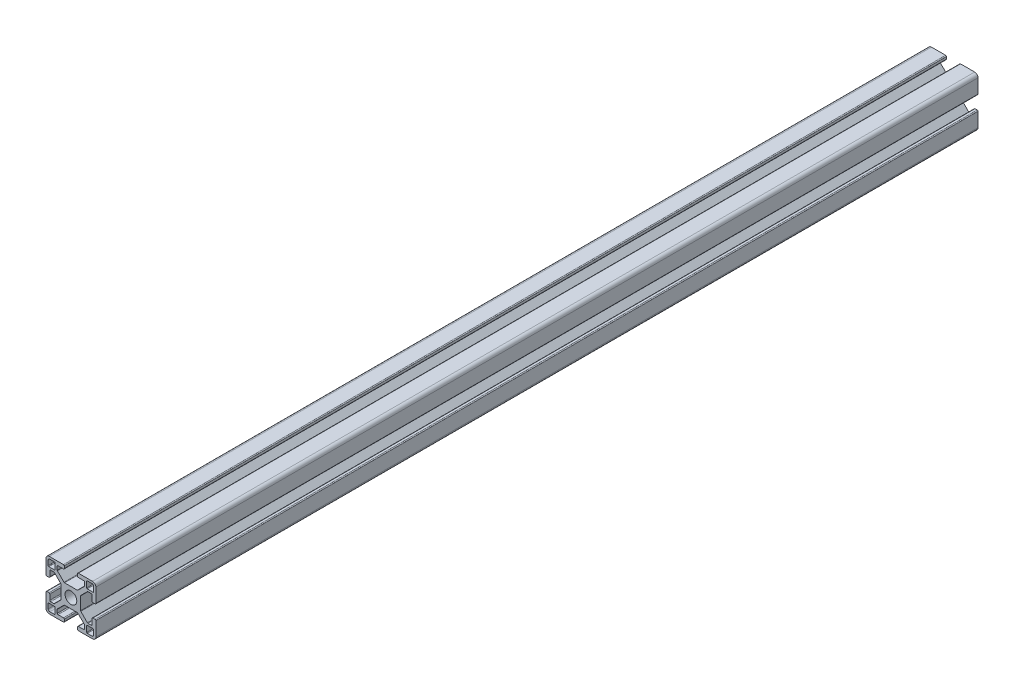
SolidWorks part; units mm, degrees
ref_plane "Front Plane" through (0, 0, 0) normal (0, 0, 1) x (1, 0, 0)
ref_plane "Top Plane" through (0, 0, 0) normal (0, 1, 0) x (1, 0, 0)
ref_plane "Right Plane" through (0, 0, 0) normal (1, 0, 0) x (0, 0, -1)
sketch "Sketch1" plane through (0, 0, 0) normal (0, 0, 1) x (1, 0, 0)
  line L0 (3.9799, -2.4733) -> (3.1981, -1.4942) construction
  line L1 (1.4942, -3.1981) -> (2.4733, -3.9799) construction
  line L2 (-2.4733, -3.9799) -> (-1.4942, -3.1981) construction
  line L3 (-3.1981, -1.4942) -> (-3.9799, -2.4733) construction
  line L4 (-3.9799, 2.4733) -> (-3.1981, 1.4942) construction
  line L5 (-1.4942, 3.1981) -> (-2.4733, 3.9799) construction
  line L6 (2.4733, 3.9799) -> (1.4942, 3.1981) construction
  line L7 (3.1981, 1.4942) -> (3.9799, 2.4733) construction
  line L8 (-12.6999, -13.6999) -> (-9.881, -13.6999)
  line L9 (-13.6999, -9.881) -> (-13.6999, -12.6999)
  line L10 (-9.88, -9.5) -> (-13.3189, -9.5)
  line L11 (-9.5, -13.3189) -> (-9.5, -9.88)
  line L12 (13.6999, -12.6999) -> (13.6999, -9.881)
  line L13 (9.881, -13.6999) -> (12.6999, -13.6999)
  line L14 (9.5, -9.88) -> (9.5, -13.3189)
  line L15 (13.3189, -9.5) -> (9.88, -9.5)
  line L16 (9.88, 9.5) -> (13.3189, 9.5)
  line L17 (9.5, 13.3189) -> (9.5, 9.88)
  line L18 (12.6999, 13.6999) -> (9.881, 13.6999)
  line L19 (13.6999, 9.881) -> (13.6999, 12.6999)
  line L20 (-13.6999, 12.6999) -> (-13.6999, 9.881)
  line L21 (-9.881, 13.6999) -> (-12.6999, 13.6999)
  line L22 (-9.5, 9.88) -> (-9.5, 13.3189)
  line L23 (-13.3189, 9.5) -> (-9.88, 9.5)
  line L24 (14.4999, -4) -> (13.2425, -4)
  line L25 (12.7425, -4.5) -> (12.7425, -7.7325)
  line L26 (12.2428, -8.25) -> (10.2602, -8.25)
  line L27 (9.9066, -8.1035) -> (5.9811, -4.178)
  line L28 (5.8347, -3.8245) -> (5.8347, -1.0125)
  line L29 (5.8347, -1.0125) -> (5.3247, -0.0625) construction
  line L30 (5.3247, -0.0625) -> (5.8347, 0.8875) construction
  line L31 (5.8347, 0.8875) -> (5.8347, 3.8245)
  line L32 (5.9811, 4.178) -> (9.9066, 8.1035)
  line L33 (10.2602, 8.25) -> (12.2428, 8.25)
  line L34 (12.7425, 7.7325) -> (12.7425, 4.5)
  line L35 (13.2425, 4) -> (14.4999, 4)
  line L36 (14.9999, 4.5) -> (14.9999, 12.9999)
  line L37 (12.9999, 14.9999) -> (4.5, 14.9999)
  line L38 (4, 14.4999) -> (4, 13.2425)
  line L39 (4.5, 12.7425) -> (7.7325, 12.7425)
  line L40 (8.25, 12.2428) -> (8.25, 10.2602)
  line L41 (8.1035, 9.9066) -> (4.178, 5.9811)
  line L42 (3.8245, 5.8347) -> (0.95, 5.8347)
  line L43 (0.95, 5.8347) -> (0, 5.3247) construction
  line L44 (0, 5.3247) -> (-0.95, 5.8347) construction
  line L45 (-0.95, 5.8347) -> (-3.8245, 5.8347)
  line L46 (-4.178, 5.9811) -> (-8.1035, 9.9066)
  line L47 (-8.25, 10.2602) -> (-8.25, 12.2428)
  line L48 (-7.7325, 12.7425) -> (-4.5, 12.7425)
  line L49 (-4, 13.2425) -> (-4, 14.4999)
  line L50 (-4.5, 14.9999) -> (-12.9999, 14.9999)
  line L51 (-14.9999, 12.9999) -> (-14.9999, 4.5)
  line L52 (-14.4999, 4) -> (-13.2425, 4)
  line L53 (-12.7425, 4.5) -> (-12.7425, 7.7325)
  line L54 (-12.2428, 8.25) -> (-10.2602, 8.25)
  line L55 (-9.9066, 8.1035) -> (-5.9811, 4.178)
  line L56 (-5.8347, 3.8245) -> (-5.8347, 0.8875)
  line L57 (-5.8347, 0.8875) -> (-5.3247, -0.0625) construction
  line L58 (-5.3247, -0.0625) -> (-5.8347, -1.0125) construction
  line L59 (-5.8347, -1.0125) -> (-5.8347, -3.8245)
  line L60 (-5.9811, -4.178) -> (-9.9066, -8.1035)
  line L61 (-10.2602, -8.25) -> (-12.2428, -8.25)
  line L62 (-12.7425, -7.7325) -> (-12.7425, -4.5)
  line L63 (-13.2425, -4) -> (-14.4999, -4)
  line L64 (-14.9999, -4.5) -> (-14.9999, -12.9999)
  line L65 (-12.9999, -14.9999) -> (-4.5, -14.9999)
  line L66 (-4, -14.4999) -> (-4, -13.2425)
  line L67 (-4.5, -12.7425) -> (-7.7325, -12.7425)
  line L68 (-8.25, -12.2428) -> (-8.25, -10.2602)
  line L69 (-8.1035, -9.9066) -> (-4.178, -5.9811)
  line L70 (-3.8245, -5.8347) -> (-0.95, -5.8347)
  line L71 (-0.95, -5.8347) -> (0, -5.3247) construction
  line L72 (0, -5.3247) -> (0.95, -5.8347) construction
  line L73 (0.95, -5.8347) -> (3.8245, -5.8347)
  line L74 (4.178, -5.9811) -> (8.1035, -9.9066)
  line L75 (8.25, -10.2602) -> (8.25, -12.2428)
  line L76 (7.7325, -12.7425) -> (4.5, -12.7425)
  line L77 (4, -13.2425) -> (4, -14.4999)
  line L78 (4.5, -14.9999) -> (12.9999, -14.9999)
  line L79 (14.9999, -12.9999) -> (14.9999, -4.5)
  line L80 (-5.8347, -1.0125) -> (-5.8347, 0.8875)
  line L81 (-0.95, 5.8347) -> (0.95, 5.8347)
  line L82 (5.8347, 0.8875) -> (5.8347, -1.0125)
  line L83 (-0.95, -5.8347) -> (0.95, -5.8347)
  arc A0 (2.4733, -3.9799) -> (3.9799, -2.4733) centre (3.1422, -3.1422) ccw construction
  arc A1 (-1.4942, -3.1981) -> (1.4942, -3.1981) centre (0, 0) ccw construction
  arc A2 (-3.9799, -2.4733) -> (-2.4733, -3.9799) centre (-3.1422, -3.1422) ccw construction
  arc A3 (-3.1981, 1.4942) -> (-3.1981, -1.4942) centre (0, 0) ccw construction
  arc A4 (-2.4733, 3.9799) -> (-3.9799, 2.4733) centre (-3.1422, 3.1422) ccw construction
  arc A5 (1.4942, 3.1981) -> (-1.4942, 3.1981) centre (0, 0) ccw construction
  arc A6 (3.9799, 2.4733) -> (2.4733, 3.9799) centre (3.1422, 3.1422) ccw construction
  arc A7 (3.1981, -1.4942) -> (3.1981, 1.4942) centre (0, 0) ccw construction
  arc A8 (-13.6999, -12.6999) -> (-12.6999, -13.6999) centre (-12.6999, -12.6999) ccw
  arc A9 (-13.3189, -9.5) -> (-13.6999, -9.881) centre (-13.3189, -9.881) ccw
  arc A10 (-9.5, -9.88) -> (-9.88, -9.5) centre (-9.88, -9.88) ccw
  arc A11 (-9.881, -13.6999) -> (-9.5, -13.3189) centre (-9.881, -13.3189) ccw
  arc A12 (12.6999, -13.6999) -> (13.6999, -12.6999) centre (12.6999, -12.6999) ccw
  arc A13 (9.5, -13.3189) -> (9.881, -13.6999) centre (9.881, -13.3189) ccw
  arc A14 (9.88, -9.5) -> (9.5, -9.88) centre (9.88, -9.88) ccw
  arc A15 (13.6999, -9.881) -> (13.3189, -9.5) centre (13.3189, -9.881) ccw
  arc A16 (9.5, 9.88) -> (9.88, 9.5) centre (9.88, 9.88) ccw
  arc A17 (9.881, 13.6999) -> (9.5, 13.3189) centre (9.881, 13.3189) ccw
  arc A18 (13.6999, 12.6999) -> (12.6999, 13.6999) centre (12.6999, 12.6999) ccw
  arc A19 (13.3189, 9.5) -> (13.6999, 9.881) centre (13.3189, 9.881) ccw
  arc A20 (14.9999, -4.5) -> (14.4999, -4) centre (14.4999, -4.5) ccw
  arc A21 (13.2425, -4) -> (12.7425, -4.5) centre (13.2425, -4.5) ccw
  arc A22 (12.2428, -8.25) -> (12.7425, -7.7325) centre (12.2428, -7.75) ccw
  arc A23 (9.9066, -8.1035) -> (10.2602, -8.25) centre (10.2602, -7.75) ccw
  arc A24 (5.8347, -3.8245) -> (5.9811, -4.178) centre (6.3347, -3.8245) ccw
  arc A25 (5.9811, 4.178) -> (5.8347, 3.8245) centre (6.3347, 3.8245) ccw
  arc A26 (10.2602, 8.25) -> (9.9066, 8.1035) centre (10.2602, 7.75) ccw
  arc A27 (12.7425, 7.7325) -> (12.2428, 8.25) centre (12.2428, 7.75) ccw
  arc A28 (12.7425, 4.5) -> (13.2425, 4) centre (13.2425, 4.5) ccw
  arc A29 (14.4999, 4) -> (14.9999, 4.5) centre (14.4999, 4.5) ccw
  arc A30 (14.9999, 12.9999) -> (12.9999, 14.9999) centre (12.9999, 12.9999) ccw
  arc A31 (4.5, 14.9999) -> (4, 14.4999) centre (4.5, 14.4999) ccw
  arc A32 (4, 13.2425) -> (4.5, 12.7425) centre (4.5, 13.2425) ccw
  arc A33 (8.25, 12.2428) -> (7.7325, 12.7425) centre (7.75, 12.2428) ccw
  arc A34 (8.1035, 9.9066) -> (8.25, 10.2602) centre (7.75, 10.2602) ccw
  arc A35 (3.8245, 5.8347) -> (4.178, 5.9811) centre (3.8245, 6.3347) ccw
  arc A36 (-4.178, 5.9811) -> (-3.8245, 5.8347) centre (-3.8245, 6.3347) ccw
  arc A37 (-8.25, 10.2602) -> (-8.1035, 9.9066) centre (-7.75, 10.2602) ccw
  arc A38 (-7.7325, 12.7425) -> (-8.25, 12.2428) centre (-7.75, 12.2428) ccw
  arc A39 (-4.5, 12.7425) -> (-4, 13.2425) centre (-4.5, 13.2425) ccw
  arc A40 (-4, 14.4999) -> (-4.5, 14.9999) centre (-4.5, 14.4999) ccw
  arc A41 (-12.9999, 14.9999) -> (-14.9999, 12.9999) centre (-12.9999, 12.9999) ccw
  arc A42 (-14.9999, 4.5) -> (-14.4999, 4) centre (-14.4999, 4.5) ccw
  arc A43 (-13.2425, 4) -> (-12.7425, 4.5) centre (-13.2425, 4.5) ccw
  arc A44 (-12.2428, 8.25) -> (-12.7425, 7.7325) centre (-12.2428, 7.75) ccw
  arc A45 (-9.9066, 8.1035) -> (-10.2602, 8.25) centre (-10.2602, 7.75) ccw
  arc A46 (-5.8347, 3.8245) -> (-5.9811, 4.178) centre (-6.3347, 3.8245) ccw
  arc A47 (-5.9811, -4.178) -> (-5.8347, -3.8245) centre (-6.3347, -3.8245) ccw
  arc A48 (-10.2602, -8.25) -> (-9.9066, -8.1035) centre (-10.2602, -7.75) ccw
  arc A49 (-12.7425, -7.7325) -> (-12.2428, -8.25) centre (-12.2428, -7.75) ccw
  arc A50 (-12.7425, -4.5) -> (-13.2425, -4) centre (-13.2425, -4.5) ccw
  arc A51 (-14.4999, -4) -> (-14.9999, -4.5) centre (-14.4999, -4.5) ccw
  arc A52 (-14.9999, -12.9999) -> (-12.9999, -14.9999) centre (-12.9999, -12.9999) ccw
  arc A53 (-4.5, -14.9999) -> (-4, -14.4999) centre (-4.5, -14.4999) ccw
  arc A54 (-4, -13.2425) -> (-4.5, -12.7425) centre (-4.5, -13.2425) ccw
  arc A55 (-8.25, -12.2428) -> (-7.7325, -12.7425) centre (-7.75, -12.2428) ccw
  arc A56 (-8.1035, -9.9066) -> (-8.25, -10.2602) centre (-7.75, -10.2602) ccw
  arc A57 (-3.8245, -5.8347) -> (-4.178, -5.9811) centre (-3.8245, -6.3347) ccw
  arc A58 (4.178, -5.9811) -> (3.8245, -5.8347) centre (3.8245, -6.3347) ccw
  arc A59 (8.25, -10.2602) -> (8.1035, -9.9066) centre (7.75, -10.2602) ccw
  arc A60 (7.7325, -12.7425) -> (8.25, -12.2428) centre (7.75, -12.2428) ccw
  arc A61 (4.5, -12.7425) -> (4, -13.2425) centre (4.5, -13.2425) ccw
  arc A62 (4, -14.4999) -> (4.5, -14.9999) centre (4.5, -14.4999) ccw
  arc A63 (12.9999, -14.9999) -> (14.9999, -12.9999) centre (12.9999, -12.9999) ccw
  arc A64 (-12.6999, 13.6999) -> (-13.6999, 12.6999) centre (-12.6999, 12.6999) ccw
  arc A65 (-9.5, 13.3189) -> (-9.881, 13.6999) centre (-9.881, 13.3189) ccw
  arc A66 (-9.88, 9.5) -> (-9.5, 9.88) centre (-9.88, 9.88) ccw
  arc A67 (-13.6999, 9.881) -> (-13.3189, 9.5) centre (-13.3189, 9.881) ccw
  circle A68 centre (0, 0) radius 3.53
extrude "Boss-Extrude1" add sketch "Sketch1" along normal mid plane 531.0221
